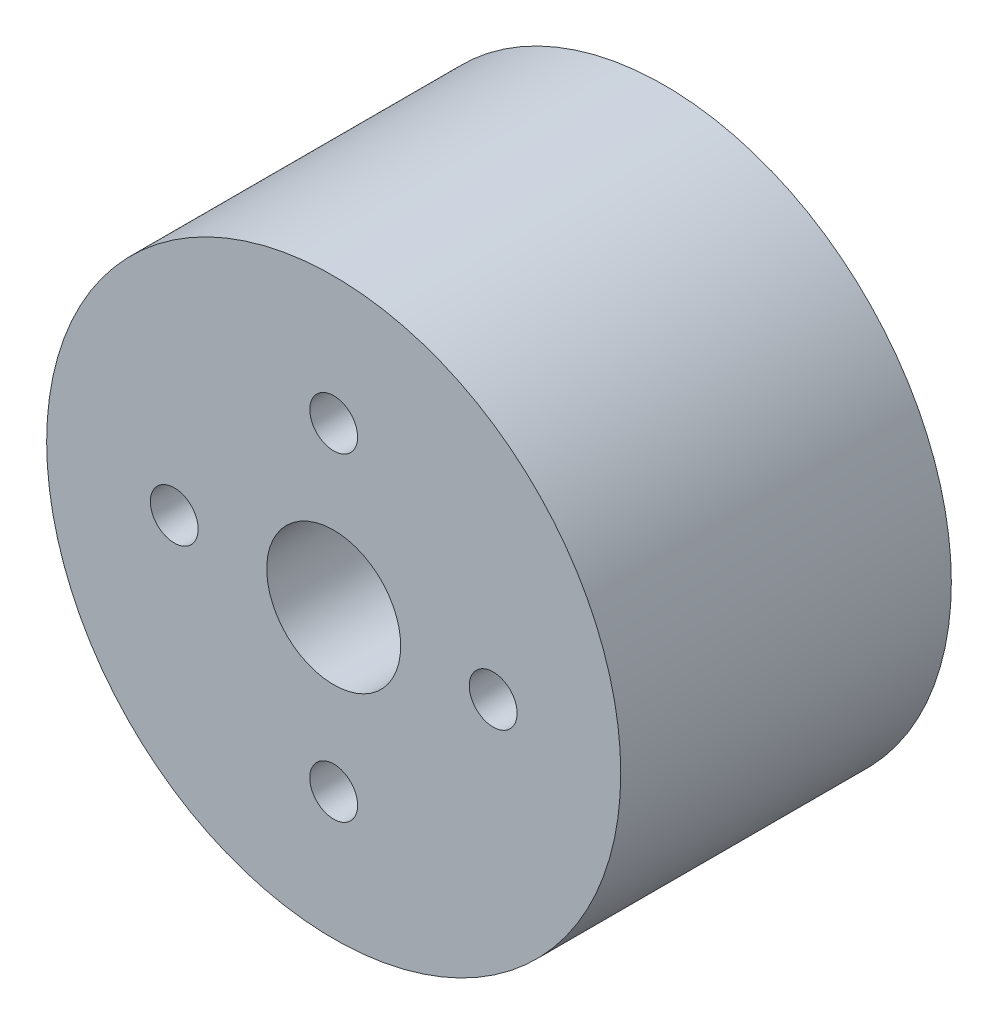
SolidWorks part; units mm, degrees
ref_plane "Front Plane" through (0, 0, 0) normal (0, 0, 1) x (1, 0, 0)
ref_plane "Top Plane" through (0, 0, 0) normal (0, 1, 0) x (1, 0, 0)
ref_plane "Right Plane" through (0, 0, 0) normal (1, 0, 0) x (0, 0, -1)
sketch "Sketch1" plane through (0, 0, 0) normal (0, 0, 1) x (1, 0, 0)
  circle A0 centre (0, 10) radius 1.5
  circle A1 centre (0, 0) radius 18
  circle A6 centre (0, 0) radius 4.2
  circle A7 centre (10, 0) radius 1.5
  circle A8 centre (0, -10) radius 1.5
  circle A9 centre (-10, 0) radius 1.5
  dimension "D1" = 4
extrude "Boss-Extrude2" add sketch "Sketch1" along normal blind 20.73
